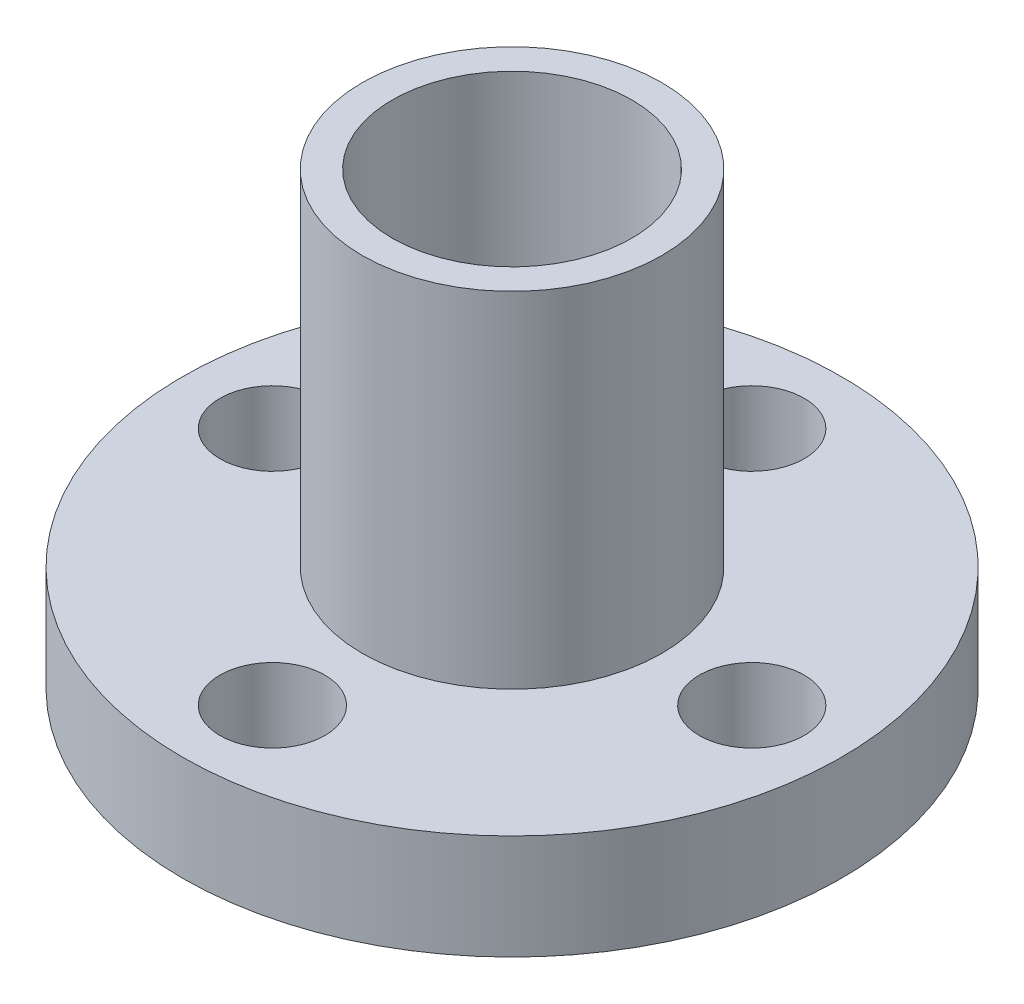
SolidWorks part; units mm, degrees
ref_plane "前视基准面" through (0, 0, 0) normal (0, 0, 1) x (1, 0, 0)
ref_plane "上视基准面" through (0, 0, 0) normal (0, 1, 0) x (1, 0, 0)
ref_plane "右视基准面" through (0, 0, 0) normal (1, 0, 0) x (0, 0, -1)
other "Configuration Table"
sketch "草图1" plane through (0, 0, 0) normal (0, 1, 0) x (1, 0, 0)
  circle A0 centre (0, 0) radius 11
  dimension "D1" = 22
extrude "凸台-拉伸1" add sketch "草图1" along normal blind 3.5
sketch "草图2" plane through (0, 3.5, 0) normal (0, 1, 0) x (1, 0, 0)
  circle A0 centre (0, 0) radius 5
  dimension "D1" = 10
extrude "凸台-拉伸2" add sketch "草图2" along normal blind 11.5
sketch "草图3" plane through (0, 15, 0) normal (0, 1, 0) x (1, 0, 0)
  circle A0 centre (0, 0) radius 4
  dimension "D1" = 8
extrude "切除-拉伸1" cut sketch "草图3" against normal through all
sketch "草图4" plane through (0, 3.5, 0) normal (0, 1, 0) x (1, 0, 0)
  circle A0 centre (0, 0) radius 8 construction
  circle A1 centre (0, 8) radius 1.75
  circle A2 centre (8, 0) radius 1.75
  circle A3 centre (0, -8) radius 1.75
  circle A4 centre (-8, 0) radius 1.75
  point P14 (0, 0)
  dimension "D1" = 16
  dimension "D2" = 3.5
  dimension "D3" = 4
extrude "切除-拉伸2" cut sketch "草图4" against normal through all
